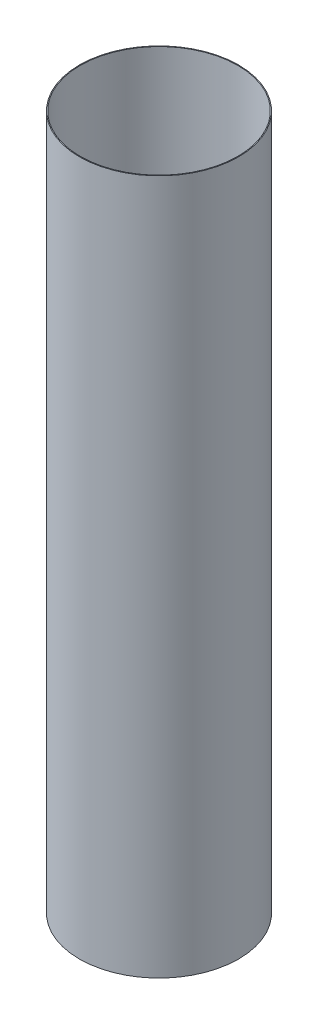
SolidWorks part; units mm, degrees
ref_plane "Front Plane" through (0, 0, 0) normal (0, 0, 1) x (1, 0, 0)
ref_plane "Top Plane" through (0, 0, 0) normal (0, 1, 0) x (1, 0, 0)
ref_plane "Right Plane" through (0, 0, 0) normal (1, 0, 0) x (0, 0, -1)
sketch "Sketch1" plane through (0, 0, 0) normal (0, 1, 0) x (1, 0, 0)
  circle A0 centre (0, 0) radius 38.1
  circle A1 centre (0, 0) radius 37.7215
  dimension "D1" = 76.2
  dimension "D2" = 0.3785
extrude "Boss-Extrude1" add sketch "Sketch1" along normal blind 332.6
